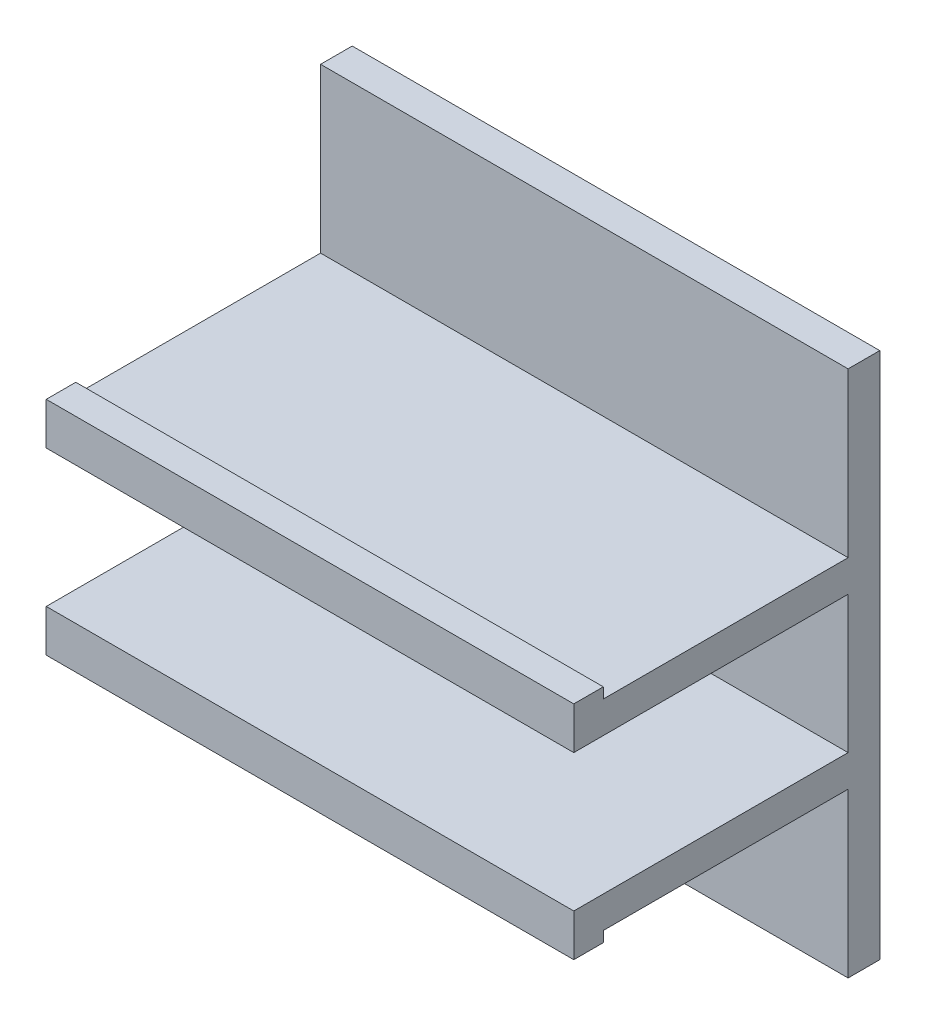
SolidWorks part; units mm, degrees
ref_plane "Спереди" through (0, 0, 0) normal (0, 0, 1) x (1, 0, 0)
ref_plane "Сверху" through (0, 0, 0) normal (0, 1, 0) x (1, 0, 0)
ref_plane "Справа" through (0, 0, 0) normal (1, 0, 0) x (0, 0, -1)
sketch "Эскиз1" plane through (0, 0, 0) normal (0, 0, 1) x (1, 0, 0)
  line L1 (0, 0) -> (25, 0)
  line L2 (0, 0) -> (0, 25)
  line L3 (0, 25) -> (25, 25)
  line L4 (25, 0) -> (25, 25)
  dimension "D1" = 25
  dimension "D2" = 25
extrude "Бобышка-Вытянуть1" add sketch "Эскиз1" along normal blind 14.5
sketch "Эскиз2" plane through (0, 0, 14.5) normal (0, 0, 1) x (1, 0, 0)
  line L0 (25, 0) -> (25, 25) construction
  line L1 (0, 25) -> (25, 25)
  line L2 (0, 25) -> (0, 17.75)
  line L3 (0, 17.75) -> (25, 17.75)
  line L4 (25, 25) -> (25, 17.75)
  line L5 (0, 25) -> (0, 0) construction
  line L6 (0, 15.75) -> (25, 15.75)
  line L7 (0, 15.75) -> (0, 9.25)
  line L8 (0, 9.25) -> (25, 9.25)
  line L9 (25, 15.75) -> (25, 9.25)
  line L10 (0, 0) -> (25, 0) construction
  line L11 (0, 7.25) -> (25, 7.25)
  line L12 (0, 7.25) -> (0, 0)
  line L13 (0, 0) -> (25, 0)
  line L14 (25, 7.25) -> (25, 0)
  dimension "D1" = 6.5
  dimension "D2" = 7.25
  dimension "D3" = 2
  dimension "D4" = 2
  dimension "D5" = 7.25
extrude "Вырез-Вытянуть1" cut sketch "Эскиз2" against normal blind 13
sketch "Эскиз3" plane through (0, 0, 1.5) normal (0, 0, 1) x (1, 0, 0)
  line L0 (25, 15.75) -> (25, 17.75) construction
  line L1 (0, 17.75) -> (25, 17.75)
  line L2 (0, 17.75) -> (0, 17.25)
  line L3 (0, 17.25) -> (25, 17.25)
  line L4 (25, 17.75) -> (25, 17.25)
  line L5 (25, 7.25) -> (25, 9.25) construction
  line L6 (0, 7.25) -> (25, 7.25)
  line L7 (0, 7.25) -> (0, 7.75)
  line L8 (0, 7.75) -> (25, 7.75)
  line L9 (25, 7.25) -> (25, 7.75)
  dimension "D1" = 0.5
  dimension "D2" = 0.5
extrude "Вырез-Вытянуть2" cut sketch "Эскиз3" along normal blind 11.6
